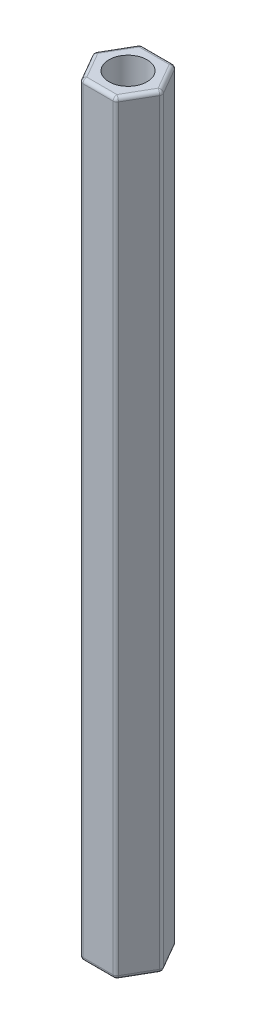
SolidWorks part; units mm, degrees
ref_plane "前视基准面" through (0, 0, 0) normal (0, 0, 1) x (1, 0, 0)
ref_plane "上视基准面" through (0, 0, 0) normal (0, 1, 0) x (1, 0, 0)
ref_plane "右视基准面" through (0, 0, 0) normal (1, 0, 0) x (0, 0, -1)
sketch "草图1" plane through (0, 0, 0) normal (0, 1, 0) x (1, 0, 0)
  line L1 (2.7135, 0) -> (1.3568, 2.35)
  line L2 (1.3568, 2.35) -> (-1.3568, 2.35)
  line L3 (-1.3568, 2.35) -> (-2.7135, 0)
  line L4 (-2.7135, 0) -> (-1.3568, -2.35)
  line L5 (-1.3568, -2.35) -> (1.3568, -2.35)
  line L6 (1.3568, -2.35) -> (2.7135, 0)
  circle A0 centre (0, 0) radius 2.35 construction
  circle A1 centre (0, 0) radius 1.5
  dimension "D1" = 4.7
extrude "凸台-拉伸1" add sketch "草图1" along normal blind 60
fillet "圆角1" radius 0.3 18 edges at (2.7135, 30, 0) (1.3568, 30, -2.35) (-1.3568, 30, -2.35) (-2.7135, 30, 0) (-1.3568, 30, 2.35) (1.3568, 30, 2.35) (0, 60, 2.35) (-2.0352, 60, 1.175) (-2.0352, 60, -1.175) (0, 60, -2.35) (2.0352, 60, -1.175) (2.0352, 60, 1.175) (0, 0, 2.35) (-2.0352, 0, 1.175) (-2.0352, 0, -1.175) (0, 0, -2.35) (2.0352, 0, -1.175) (2.0352, 0, 1.175)
